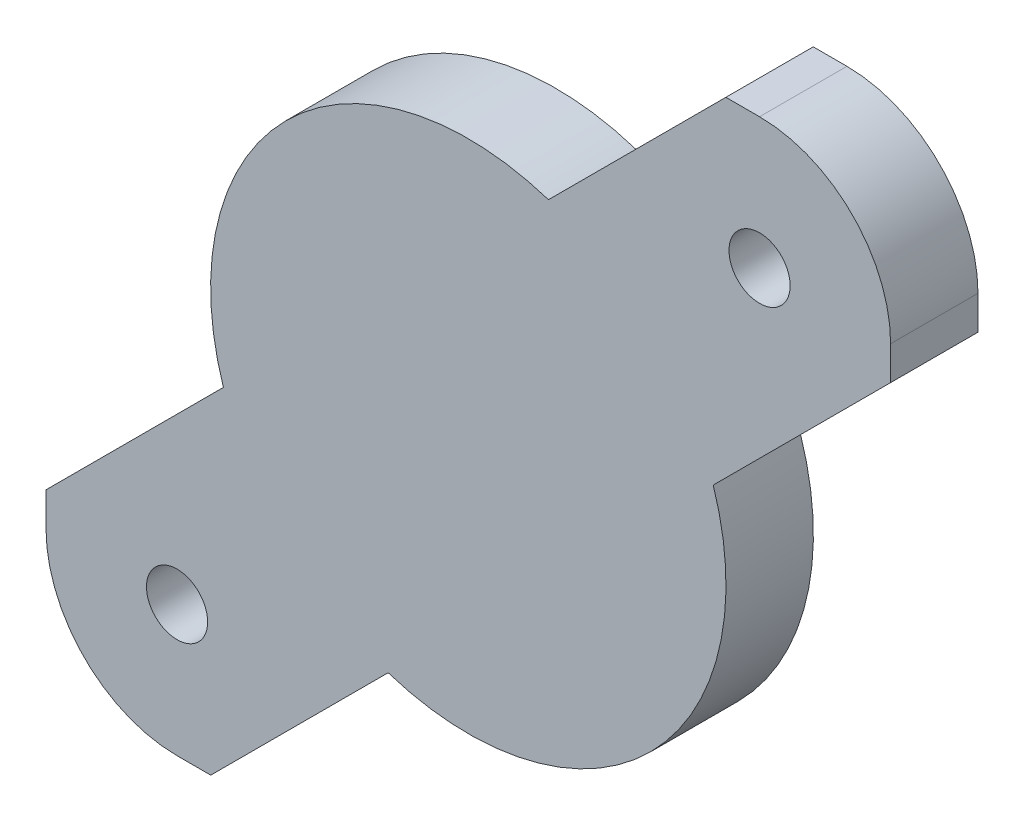
SolidWorks part; units mm, degrees
ref_plane "Front Plane" through (0, 0, 0) normal (0, 0, 1) x (1, 0, 0)
ref_plane "Top Plane" through (0, 0, 0) normal (0, 1, 0) x (1, 0, 0)
ref_plane "Right Plane" through (0, 0, 0) normal (1, 0, 0) x (0, 0, -1)
sketch "Sketch1" plane through (0, 0, 0) normal (0, 0, 1) x (1, 0, 0)
  line L7 (2.7525, 8.4093) -> (8.8431, 14.5)
  line L8 (-8.4093, -2.7525) -> (-14.5, -8.8431)
  line L9 (-2.7525, -8.4093) -> (-8.8431, -14.5)
  line L10 (14.5, 10) -> (14.5, -10)
  line L11 (-10, 14.5) -> (10, 14.5)
  line L12 (-14.5, -10) -> (-14.5, 10)
  line L13 (14.5, 10) -> (14.5, 8.8431)
  line L14 (8.8431, 14.5) -> (10, 14.5)
  line L15 (-14.5, -10) -> (-14.5, -8.8431)
  line L16 (-10, -14.5) -> (-8.8431, -14.5)
  line L17 (8.4093, 2.7525) -> (14.5, 8.8431)
  circle A1 centre (10, 10) radius 1.05
  circle A2 centre (-10, -10) radius 1.05
  arc A3 (-2.7525, -8.4093) -> (8.4093, 2.7525) centre (0, 0) ccw
  arc A4 (2.7525, 8.4093) -> (-8.4093, -2.7525) centre (0, 0) ccw
  arc A24 (-10, 14.5) -> (-14.5, 10) centre (-10, 10) ccw
  arc A25 (-14.5, -10) -> (-10, -14.5) centre (-10, -10) ccw
  arc A26 (14.5, 10) -> (10, 14.5) centre (10, 10) ccw
  arc A28 (-14.5, -10) -> (-10, -14.5) centre (-10, -10) ccw
  arc A29 (14.5, 10) -> (10, 14.5) centre (10, 10) ccw
  dimension "D1" = 2.1
  dimension "D2" = 2.1
  dimension "D3" = 0.5
extrude "Boss-Extrude1" add sketch "Sketch1" along normal blind 3
